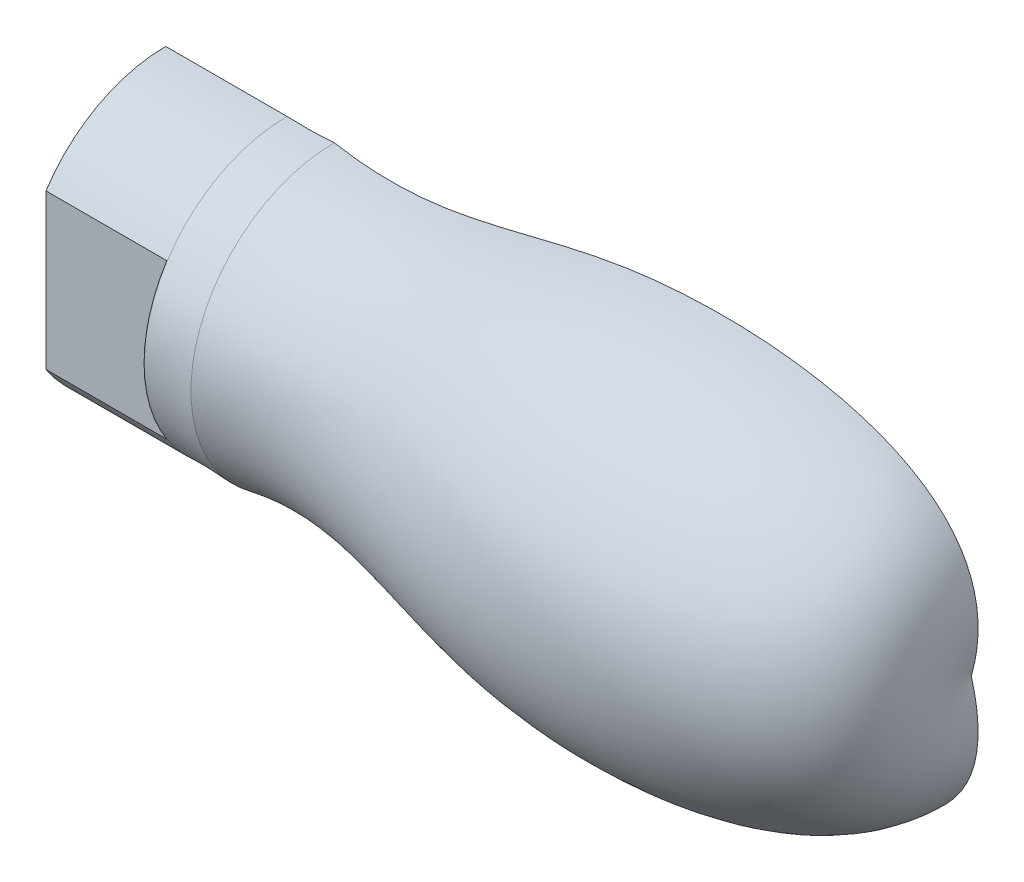
SolidWorks part; units mm, degrees
ref_plane "Front Plane" through (0, 0, 0) normal (0, 0, 1) x (1, 0, 0)
ref_plane "Top Plane" through (0, 0, 0) normal (0, 1, 0) x (1, 0, 0)
ref_plane "Right Plane" through (0, 0, 0) normal (1, 0, 0) x (0, 0, -1)
other "Graphic1"
other "Graphic (Closed) -1"
sketch "Sketch2" plane through (0, 0, 0) normal (0, 1, 0) x (1, 0, 0)
  line L1 (-0.0409, 0.02) -> (0.06, 0.02)
  line L2 (-0.0409, -0.0023) -> (-0.0219, -0.0023)
  line L3 (0.06, 0.02) -> (0.085, 0.02)
  line L4 (-0.0409, -0.0023) -> (-0.0409, 0.02)
  spline S0 degree 2 poles (-0.0219, -0.0023) (-0.0182, -0.0021) (-0.0145, -0.0024) knots 0 0 0 0.074407 0.074407 0.074407
  spline S1 degree 3 poles (0.085, 0.02) (0.0927, -0.0069) (0.0323, -0.0155) (0.0025, 0.0007) (-0.0145, -0.0024) knots 0 0 0 0 0.593317 1 1 1 1
revolve "Revolve2" add sketch "Sketch2" angle 90 about L1
ref_plane "Plane1" through (-0.022, 0, 0) normal (1, 0, 0) x (0, 0, -1)
sketch "Sketch4" plane through (-0.022, 0, 0) normal (1, 0, 0) x (0, 0, -1)
  line L1 (-0.0134, 0.0169) -> (0.0013, 0.0169)
  line L2 (-0.0134, 0.0169) -> (-0.0134, -0.0169)
  line L3 (-0.0134, -0.0169) -> (0.0013, -0.0169)
  line L4 (0.0013, 0.0169) -> (0.0013, -0.0169)
  line L5 (-0.0134, 0.0169) -> (0.0013, -0.0169) construction
  line L6 (-0.0134, -0.0169) -> (0.0013, 0.0169) construction
  point P0 (-0.0061, 0)
extrude "Cut-Extrude1" cut sketch "Sketch4" against normal blind 10
